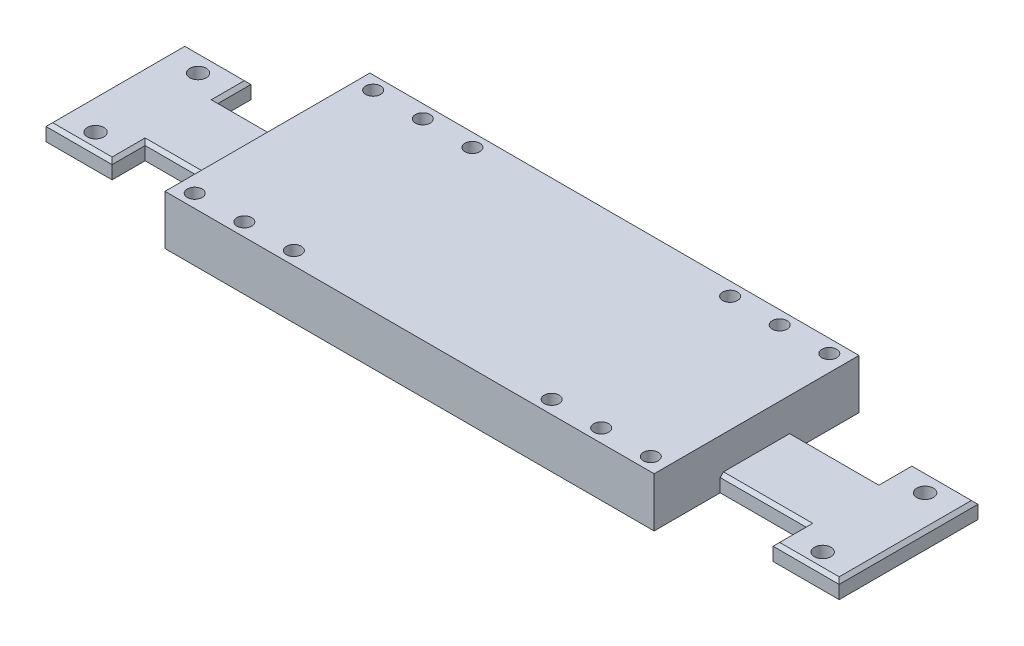
SolidWorks part; units mm, degrees
ref_plane "Front Plane" through (0, 0, 0) normal (0, 0, 1) x (1, 0, 0)
ref_plane "Top Plane" through (0, 0, 0) normal (0, 1, 0) x (1, 0, 0)
ref_plane "Right Plane" through (0, 0, 0) normal (1, 0, 0) x (0, 0, -1)
sketch "Sketch1" plane through (0, 0, 0) normal (0, 1, 0) x (1, 0, 0)
  line L1 (0, 0) -> (148, 0)
  line L2 (0, 0) -> (0, 62)
  line L3 (0, 62) -> (148, 62)
  line L4 (148, 0) -> (148, 62)
extrude "Boss-Extrude1" add sketch "Sketch1" along normal blind 15
sketch "Sketch2" plane through (0, 15, 0) normal (0, 1, 0) x (1, 0, 0)
  circle A0 centre (5, 4) radius 2.25
  circle A1 centre (20, 4) radius 2.25
  circle A2 centre (35, 4) radius 2.25
  circle A3 centre (5, 58) radius 2.25
  circle A4 centre (20, 58) radius 2.25
  circle A5 centre (35, 58) radius 2.25
extrude "Cut-Extrude1" cut sketch "Sketch2" against normal blind 35
sketch "Sketch3" plane through (0, 15, 0) normal (0, 1, 0) x (1, 0, 0)
  circle A0 centre (143, 58) radius 2.25
  circle A1 centre (143, 4) radius 2.25
  circle A2 centre (128, 58) radius 2.25
  circle A3 centre (113, 58) radius 2.25
  circle A4 centre (128, 4) radius 2.25
  circle A5 centre (113, 4) radius 2.25
extrude "Cut-Extrude2" cut sketch "Sketch3" against normal blind 25
sketch "Sketch4" plane through (148, 0, 0) normal (1, 0, 0) x (0, 0, -1)
  line L1 (42, 5) -> (20, 5)
  line L2 (42, 5) -> (42, 0)
  line L3 (42, 0) -> (20, 0)
  line L4 (20, 5) -> (20, 0)
extrude "Boss-Extrude2" add sketch "Sketch4" along normal blind 26
sketch "Sketch5" plane through (0, 0, 0) normal (-1, 0, 0) x (0, 0, 1)
  line L1 (-42, 0) -> (-20, 0)
  line L2 (-42, 0) -> (-42, 5)
  line L3 (-42, 5) -> (-20, 5)
  line L4 (-20, 0) -> (-20, 5)
extrude "Boss-Extrude3" add sketch "Sketch5" along normal blind 26
sketch "Sketch6" plane through (0, 15, 0) normal (0, 1, 0) x (1, 0, 0)
  line L1 (174, 52) -> (194, 52)
  line L2 (174, 52) -> (174, 10)
  line L3 (174, 10) -> (194, 10)
  line L4 (194, 52) -> (194, 10)
extrude "Boss-Extrude4" add sketch "Sketch6" against normal blind 15
sketch "Sketch7" plane through (0, 15, 0) normal (0, 1, 0) x (1, 0, 0)
  line L1 (-26, 52) -> (-46, 52)
  line L2 (-26, 52) -> (-26, 10)
  line L3 (-26, 10) -> (-46, 10)
  line L4 (-46, 52) -> (-46, 10)
extrude "Boss-Extrude5" add sketch "Sketch7" against normal up to vertex (15 mm away)
sketch "Sketch8" plane through (0, 15, 0) normal (0, 1, 0) x (1, 0, 0)
  circle A0 centre (-36, 46) radius 2.5
  circle A1 centre (-36, 15) radius 2.5
extrude "Cut-Extrude3" cut sketch "Sketch8" against normal blind 25
sketch "Sketch9" plane through (0, 15, 0) normal (0, 1, 0) x (1, 0, 0)
  circle A0 centre (184, 46) radius 2.5
  circle A1 centre (184, 15) radius 2.5
extrude "Cut-Extrude4" cut sketch "Sketch9" against normal blind 25
chamfer "Chamfer3" distance 1 angle 45 4 edges at (161, 5, -20) (194, 15, -31) (-26, 15, -31) (-46, 15, -31)
chamfer "Chamfer4" distance 1 angle 45 6 edges at (-13, 5, -20) (-36, 15, -10) (-36, 15, -52) (183.5, 15, -10) (183.5, 15, -52) (161, 5, -42)
chamfer "Chamfer5" distance 1 angle 45 2 edges at (-13, 5, -42) (174, 15, -31)
sketch "Sketch10" plane through (0, 0, -52) normal (0, 0, -1) x (-1, 0, 0)
  line L1 (-170, 5) -> (-197.5308, 5)
  line L2 (-170, 5) -> (-170, 19.1737)
  line L3 (-170, 19.1737) -> (-197.5308, 19.1737)
  line L4 (-197.5308, 5) -> (-197.5308, 19.1737)
extrude "Cut-Extrude5" cut sketch "Sketch10" against normal blind 60
sketch "Sketch11" plane through (0, 0, -52) normal (0, 0, -1) x (-1, 0, 0)
  line L1 (21.4765, 5) -> (53.9717, 5)
  line L2 (21.4765, 5) -> (21.4765, 20.92)
  line L3 (21.4765, 20.92) -> (53.9717, 20.92)
  line L4 (53.9717, 5) -> (53.9717, 20.92)
extrude "Cut-Extrude6" cut sketch "Sketch11" against normal blind 60
chamfer "Chamfer6" distance 1 angle 45 6 edges at (174, 5, -46.5) (194, 5, -31) (174, 5, -15.5) (-46, 5, -31) (-36, 5, -10) (-26, 5, -46.5)
chamfer "Chamfer7" distance 1 angle 45 4 edges at (-36, 5, -52) (-26, 5, -16) (184, 5, -10) (184, 5, -52)
